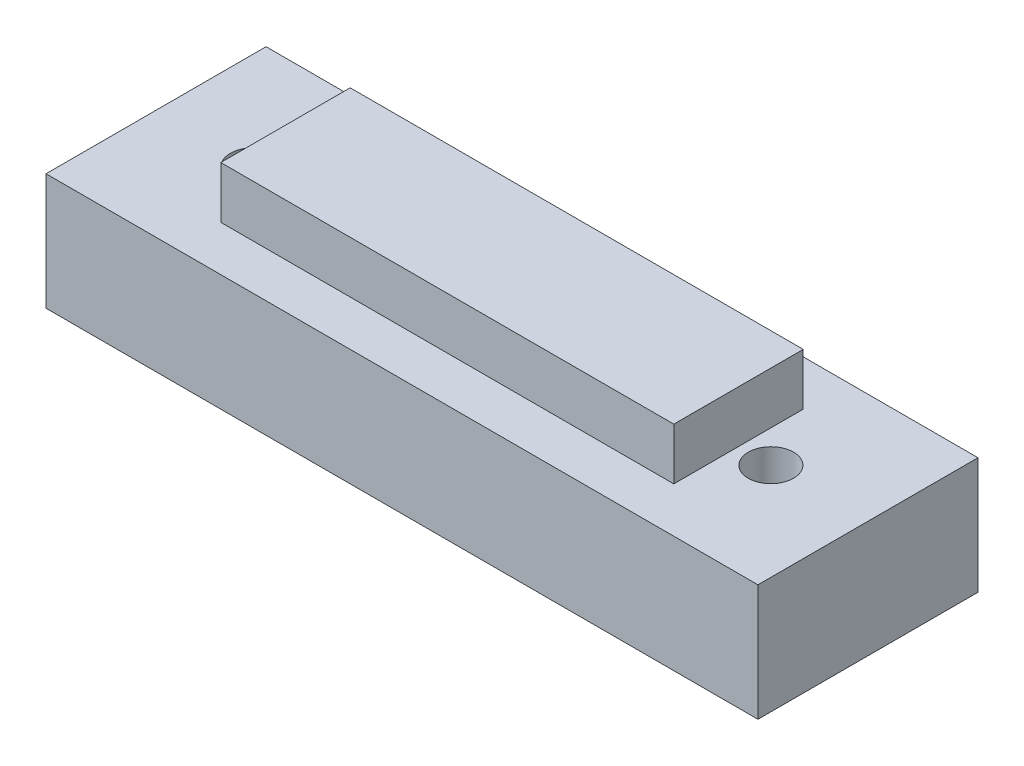
SolidWorks part; units mm, degrees
ref_plane "前视基准面" through (0, 0, 0) normal (0, 0, 1) x (1, 0, 0)
ref_plane "上视基准面" through (0, 0, 0) normal (0, 1, 0) x (1, 0, 0)
ref_plane "右视基准面" through (0, 0, 0) normal (1, 0, 0) x (0, 0, -1)
other "Configuration Table"
sketch "01_Base_Profile" plane through (0, 0, 0) normal (0, 1, 0) x (1, 0, 0)
  line L1 (-55, -17) -> (55, -17)
  line L2 (-55, -17) -> (-55, 17)
  line L3 (-55, 17) -> (55, 17)
  line L4 (55, -17) -> (55, 17)
  line L5 (-55, -17) -> (55, 17) construction
  line L6 (-55, 17) -> (55, -17) construction
  circle A0 centre (-40, 0) radius 3.5
  circle A1 centre (40, 0) radius 3.5
  point P0 (0, 0)
extrude "01_Base_Extrude" add sketch "01_Base_Profile" along normal blind 18
sketch "02_Boss_Profile" plane through (0, 0, 0) normal (0, 1, 0) x (1, 0, 0)
  line L1 (-35, -10) -> (35, -10)
  line L2 (-35, -10) -> (-35, 10)
  line L3 (-35, 10) -> (35, 10)
  line L4 (35, -10) -> (35, 10)
  line L5 (-35, -10) -> (35, 10) construction
  line L6 (-35, 10) -> (35, -10) construction
  point P0 (0, 0)
extrude "02_Reinforcement_Boss" add sketch "02_Boss_Profile" along normal blind 26
